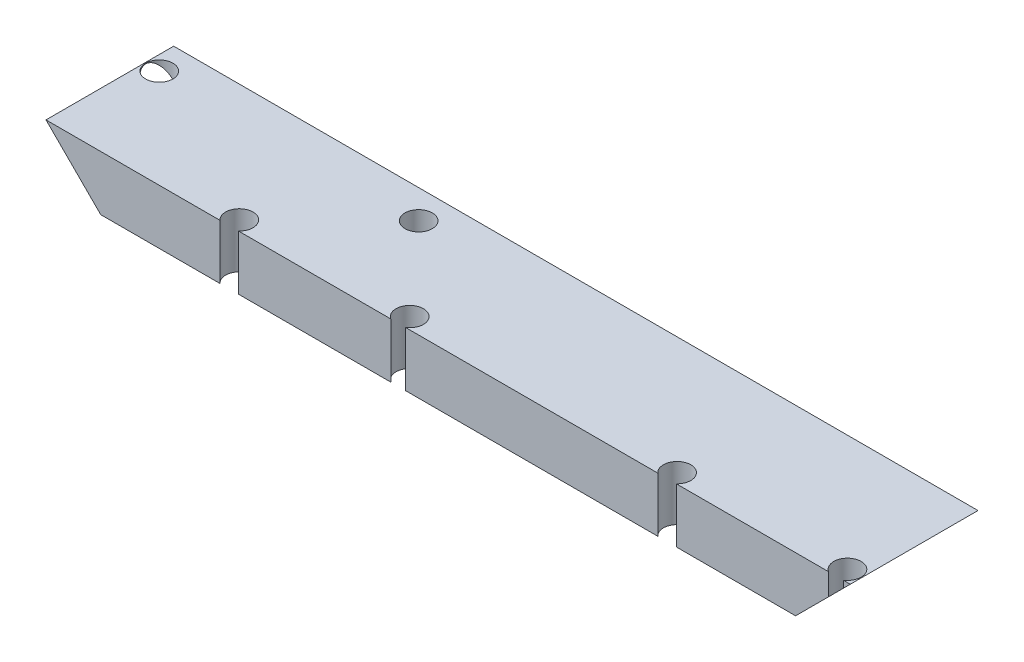
SolidWorks part; units mm, degrees
ref_plane "Front Plane" through (0, 0, 0) normal (0, 0, 1) x (1, 0, 0)
ref_plane "Top Plane" through (0, 0, 0) normal (0, 1, 0) x (1, 0, 0)
ref_plane "Right Plane" through (0, 0, 0) normal (1, 0, 0) x (0, 0, -1)
sketch "Sketch1" plane through (0, 0, 0) normal (0, 1, 0) x (1, 0, 0)
  line L0 (560, 430) -> (560, 10) construction
  line L1 (0, 88.9) -> (560, 88.9)
  line L2 (0, 88.9) -> (0, 0)
  line L3 (0, 0) -> (560, 0)
  line L4 (560, 88.9) -> (560, 0)
  dimension "D1" = 88.9
extrude "Body" add sketch "Sketch1" along normal blind 38.1
sketch "Sketch2" plane through (0, 38.1, 0) normal (0, 1, 0) x (1, 0, 0)
  circle A0 centre (127.6, 7) radius 9.525
  circle A2 centre (190.57, 68.87) radius 9.525
  circle A3 centre (10, 68.87) radius 9.525
  circle A4 centre (245.2, 8.02) radius 9.525
  circle A5 centre (550, 8.02) radius 9.525
  circle A7 centre (432.4, 7) radius 9.525
  dimension "D1" = 19.05
extrude "Mounting hole spacing" cut sketch "Sketch2" against normal up to next
sketch "Sketch3" plane through (0, 0, -88.9) normal (0, 0, -1) x (-1, 0, 0)
  line L0 (-560, 0) -> (-560, 38.1)
  line L1 (-560, 0) -> (-521.9, 0)
  line L2 (-560, 38.1) -> (0, 38.1) construction
  line L3 (-521.9, 0) -> (-560, 38.1)
  line L4 (-280, 0) -> (-280, 38.1) construction
  line L5 (-560, 0) -> (0, 0) construction
  line L8 (0, 0) -> (0, 38.1)
  line L9 (-38.1, 0) -> (0, 38.1)
  line L10 (0, 0) -> (-38.1, 0)
extrude "Cut-Extrude1" cut sketch "Sketch3" against normal up to next
